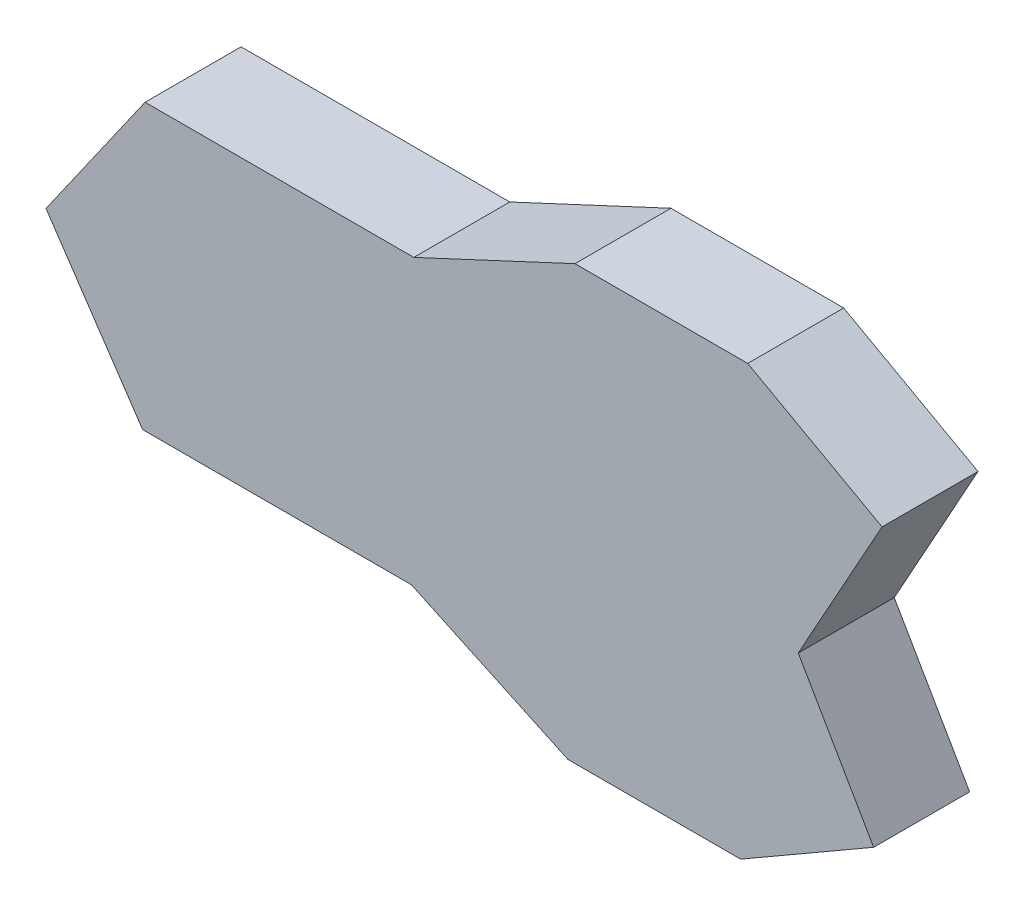
SolidWorks part; units mm, degrees
ref_plane "Front Plane" through (0, 0, 0) normal (0, 0, 1) x (1, 0, 0)
ref_plane "Top Plane" through (0, 0, 0) normal (0, 1, 0) x (1, 0, 0)
ref_plane "Right Plane" through (0, 0, 0) normal (1, 0, 0) x (0, 0, -1)
sketch "Sketch1" plane through (0, 0, 0) normal (0, 0, 1) x (1, 0, 0)
  line L0 (0, 0) -> (-355.6, 0)
  line L1 (-355.6, 0) -> (-483.4315, 189.518)
  line L2 (-483.4315, 189.518) -> (-352.3119, 376.7761)
  line L3 (-352.3119, 376.7761) -> (3.2881, 376.7761)
  line L4 (0, 0) -> (207.182, -96.6105)
  line L5 (207.182, -96.6105) -> (435.782, -96.6105)
  line L6 (435.782, -96.6105) -> (611.7583, 4.9895)
  line L7 (611.7583, 4.9895) -> (512.0121, 177.755)
  line L8 (512.0121, 177.755) -> (622.8396, 377.693)
  line L9 (622.8396, 377.693) -> (445.1169, 476.2064)
  line L10 (445.1169, 476.2064) -> (216.5169, 476.2064)
  line L11 (216.5169, 476.2064) -> (3.2881, 376.7761)
  dimension "D1" = 355.6
  dimension "D2" = 228.6
  dimension "D3" = 228.6
  dimension "D4" = 111
  dimension "D5" = 125
  dimension "D6" = 355.6
  dimension "D7" = 155
  dimension "D8" = 228.6
  dimension "D9" = 228.6
  dimension "D10" = 150
  dimension "D11" = 203.2
  dimension "D12" = 90
  dimension "D13" = 121
  dimension "D14" = 228.6
  dimension "D15" = 90
  dimension "D16" = 203.2
  dimension "D17" = 228.6
  dimension "D18" = 155
extrude "Boss-Extrude1" add sketch "Sketch1" along normal mid plane 127
